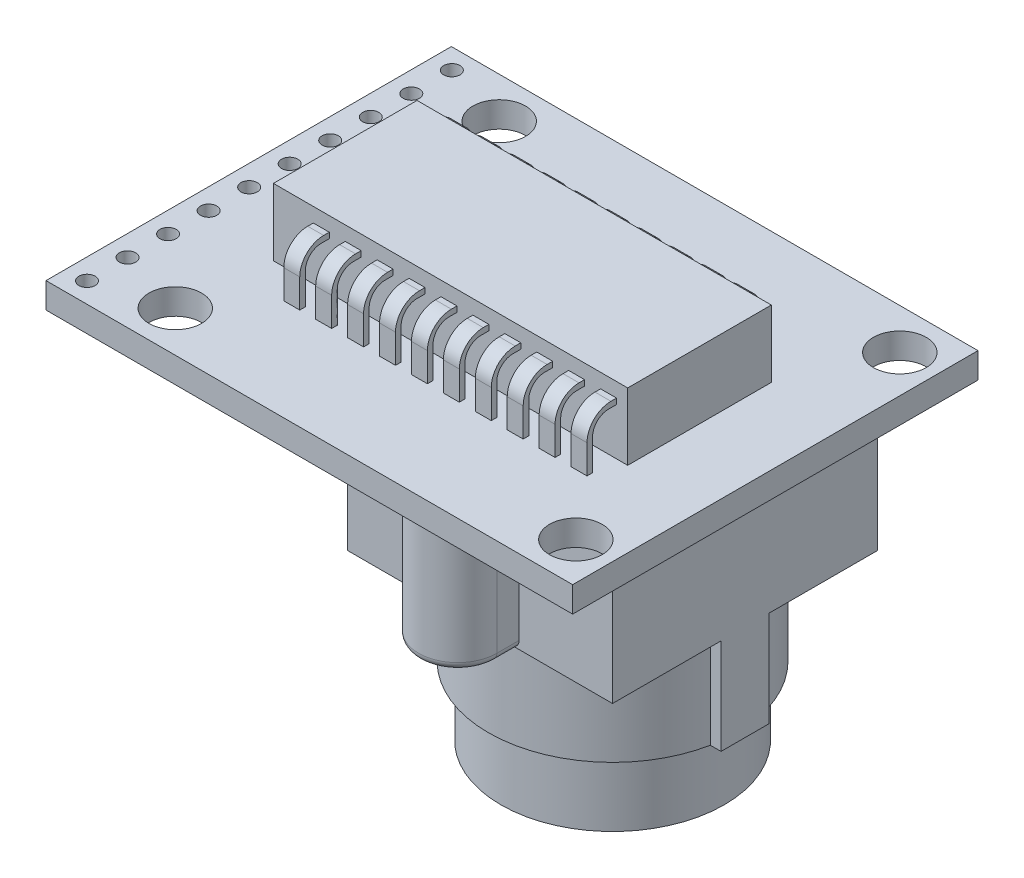
SolidWorks part; units mm, degrees
ref_plane "Alzado" through (0, 0, 0) normal (0, 0, 1) x (1, 0, 0)
ref_plane "Planta" through (0, 0, 0) normal (0, 1, 0) x (1, 0, 0)
ref_plane "Vista lateral" through (0, 0, 0) normal (1, 0, 0) x (0, 0, -1)
sketch "Croquis1" plane through (0, 0, 0) normal (0, 1, 0) x (1, 0, 0)
  line L0 (-6.0979, 0) -> (20.9271, 0) construction
  line L1 (-16.5, -12.7) -> (16.5, -12.7)
  line L2 (-16.5, -12.7) -> (-16.5, 12.7)
  line L3 (-16.5, 12.7) -> (16.5, 12.7)
  line L4 (16.5, -12.7) -> (16.5, 12.7)
  line L5 (-16.5, -12.7) -> (16.5, 12.7) construction
  line L6 (-16.5, 12.7) -> (16.5, -12.7) construction
  circle A0 centre (-15.2, 11.43) radius 0.51
  circle A1 centre (-15.2, 8.89) radius 0.51
  circle A2 centre (-15.2, 6.35) radius 0.51
  circle A3 centre (-15.2, 3.81) radius 0.51
  circle A4 centre (-15.2, 1.27) radius 0.51
  circle A5 centre (-15.2, -1.27) radius 0.51
  circle A6 centre (-15.2, -3.81) radius 0.51
  circle A7 centre (-15.2, -6.35) radius 0.51
  circle A8 centre (-15.2, -8.89) radius 0.51
  circle A9 centre (-15.2, -11.43) radius 0.51
  circle A10 centre (14.15, 10.15) radius 1.65
  circle A11 centre (14.15, -10.15) radius 1.65
  circle A12 centre (-10.95, 10.15) radius 1.65
  circle A13 centre (-10.95, -10.15) radius 1.65
  point P0 (0, 0)
  dimension "D3" = 1.02
  dimension "D4" = 1.3
  dimension "D5" = 1.27
  dimension "D7" = 3.3
  dimension "D8" = 2.35
  dimension "D9" = 2.55
  dimension "D10" = 3.3
  dimension "D11" = 5.55
  dimension "D12" = 2.55
  dimension "D1" = 25.4
  dimension "D2" = 33
  dimension "D6" = 10
extrude "Saliente-Extruir1" add sketch "Croquis1" along normal blind 1.6
sketch "Croquis2" plane through (0, 1.6, 0) normal (0, 1, 0) x (1, 0, 0)
  line L0 (-19.1826, 0) -> (21.3671, 0) construction
  line L1 (16.5, -12.7) -> (16.5, 12.7) construction
  line L2 (-10.45, -4.5) -> (11.75, -4.5)
  line L3 (-10.45, -4.5) -> (-10.45, 4.5)
  line L4 (-10.45, 4.5) -> (11.75, 4.5)
  line L5 (11.75, -4.5) -> (11.75, 4.5)
  line L6 (-10.45, -4.5) -> (11.75, 4.5) construction
  line L7 (-10.45, 4.5) -> (11.75, -4.5) construction
  point P3 (0.65, 0)
  dimension "D1" = 22.2
  dimension "D2" = 9
  dimension "D3" = 4.75
extrude "Saliente-Extruir2" add sketch "Croquis2" along normal blind 4.2
sketch "Croquis3" plane through (0, 1.6, 0) normal (0, 1, 0) x (1, 0, 0)
  line L0 (-10.45, -4.5) -> (11.75, -4.5) construction
  line L1 (10.05, -6) -> (11.05, -6)
  line L2 (10.05, -6) -> (10.05, -6.35)
  line L3 (10.05, -6.35) -> (11.05, -6.35)
  line L4 (11.05, -6) -> (11.05, -6.35)
  line L5 (11.75, -4.5) -> (11.75, 4.5) construction
  line L6 (8.05, -6) -> (8.05, -6.35)
  line L7 (8.05, -6) -> (9.05, -6)
  line L8 (9.05, -6) -> (9.05, -6.35)
  line L9 (8.05, -6.35) -> (9.05, -6.35)
  line L10 (6.05, -6) -> (6.05, -6.35)
  line L11 (6.05, -6) -> (7.05, -6)
  line L12 (7.05, -6) -> (7.05, -6.35)
  line L13 (6.05, -6.35) -> (7.05, -6.35)
  line L14 (4.05, -6) -> (4.05, -6.35)
  line L15 (4.05, -6) -> (5.05, -6)
  line L16 (5.05, -6) -> (5.05, -6.35)
  line L17 (4.05, -6.35) -> (5.05, -6.35)
  line L18 (2.05, -6) -> (2.05, -6.35)
  line L19 (2.05, -6) -> (3.05, -6)
  line L20 (3.05, -6) -> (3.05, -6.35)
  line L21 (2.05, -6.35) -> (3.05, -6.35)
  line L22 (0.05, -6) -> (0.05, -6.35)
  line L23 (0.05, -6) -> (1.05, -6)
  line L24 (1.05, -6) -> (1.05, -6.35)
  line L25 (0.05, -6.35) -> (1.05, -6.35)
  line L26 (-1.95, -6) -> (-1.95, -6.35)
  line L27 (-1.95, -6) -> (-0.95, -6)
  line L28 (-0.95, -6) -> (-0.95, -6.35)
  line L29 (-1.95, -6.35) -> (-0.95, -6.35)
  line L30 (-3.95, -6) -> (-3.95, -6.35)
  line L31 (-3.95, -6) -> (-2.95, -6)
  line L32 (-2.95, -6) -> (-2.95, -6.35)
  line L33 (-3.95, -6.35) -> (-2.95, -6.35)
  line L34 (-5.95, -6) -> (-5.95, -6.35)
  line L35 (-5.95, -6) -> (-4.95, -6)
  line L36 (-4.95, -6) -> (-4.95, -6.35)
  line L37 (-5.95, -6.35) -> (-4.95, -6.35)
  line L38 (-7.95, -6) -> (-7.95, -6.35)
  line L39 (-7.95, -6) -> (-6.95, -6)
  line L40 (-6.95, -6) -> (-6.95, -6.35)
  line L41 (-7.95, -6.35) -> (-6.95, -6.35)
  line L43 (-10.45, 4.5) -> (-10.45, -4.5) construction
  line L44 (-9.75, 6.35) -> (-8.75, 6.35)
  line L45 (-9.75, 6.35) -> (-9.75, 6)
  line L46 (-9.75, 6) -> (-8.75, 6)
  line L47 (-8.75, 6.35) -> (-8.75, 6)
  line L48 (11.75, 4.5) -> (-10.45, 4.5) construction
  line L49 (-7.75, 6.35) -> (-7.75, 6)
  line L50 (-7.75, 6.35) -> (-6.75, 6.35)
  line L51 (-6.75, 6.35) -> (-6.75, 6)
  line L52 (-7.75, 6) -> (-6.75, 6)
  line L53 (-5.75, 6.35) -> (-5.75, 6)
  line L54 (-5.75, 6.35) -> (-4.75, 6.35)
  line L55 (-4.75, 6.35) -> (-4.75, 6)
  line L56 (-5.75, 6) -> (-4.75, 6)
  line L57 (-3.75, 6.35) -> (-3.75, 6)
  line L58 (-3.75, 6.35) -> (-2.75, 6.35)
  line L59 (-2.75, 6.35) -> (-2.75, 6)
  line L60 (-3.75, 6) -> (-2.75, 6)
  line L61 (-1.75, 6.35) -> (-1.75, 6)
  line L62 (-1.75, 6.35) -> (-0.75, 6.35)
  line L63 (-0.75, 6.35) -> (-0.75, 6)
  line L64 (-1.75, 6) -> (-0.75, 6)
  line L65 (0.25, 6.35) -> (0.25, 6)
  line L66 (0.25, 6.35) -> (1.25, 6.35)
  line L67 (1.25, 6.35) -> (1.25, 6)
  line L68 (0.25, 6) -> (1.25, 6)
  line L69 (2.25, 6.35) -> (2.25, 6)
  line L70 (2.25, 6.35) -> (3.25, 6.35)
  line L71 (3.25, 6.35) -> (3.25, 6)
  line L72 (2.25, 6) -> (3.25, 6)
  line L73 (4.25, 6.35) -> (4.25, 6)
  line L74 (4.25, 6.35) -> (5.25, 6.35)
  line L75 (5.25, 6.35) -> (5.25, 6)
  line L76 (4.25, 6) -> (5.25, 6)
  line L77 (6.25, 6.35) -> (6.25, 6)
  line L78 (6.25, 6.35) -> (7.25, 6.35)
  line L79 (7.25, 6.35) -> (7.25, 6)
  line L80 (6.25, 6) -> (7.25, 6)
  line L81 (8.25, 6.35) -> (8.25, 6)
  line L82 (8.25, 6.35) -> (9.25, 6.35)
  line L83 (9.25, 6.35) -> (9.25, 6)
  line L84 (8.25, 6) -> (9.25, 6)
  dimension "D1" = 0.35
  dimension "D2" = 1
  dimension "D3" = 1.5
  dimension "D4" = 0.7
  dimension "D6" = 0.35
  dimension "D7" = 1
  dimension "D8" = 0.7
  dimension "D9" = 1.5
  dimension "D5" = 10
  dimension "D10" = 10
extrude "Saliente-Extruir3" add sketch "Croquis3" along normal blind 3.3
sketch "Croquis4" plane through (0, 0, 6) normal (0, 0, -1) x (-1, 0, 0)
  line L0 (-10.05, 4.9) -> (-10.05, 1.6) construction
  line L1 (-11.05, 4.9) -> (-10.05, 4.9)
  line L2 (-11.05, 4.9) -> (-11.05, 4.55)
  line L3 (-11.05, 4.55) -> (-10.05, 4.55)
  line L4 (-10.05, 4.9) -> (-10.05, 4.55)
  line L5 (-9.05, 4.9) -> (-9.05, 4.55)
  line L6 (-9.05, 4.9) -> (-8.05, 4.9)
  line L7 (-8.05, 4.9) -> (-8.05, 4.55)
  line L8 (-9.05, 4.55) -> (-8.05, 4.55)
  line L9 (-7.05, 4.9) -> (-7.05, 4.55)
  line L10 (-7.05, 4.9) -> (-6.05, 4.9)
  line L11 (-6.05, 4.9) -> (-6.05, 4.55)
  line L12 (-7.05, 4.55) -> (-6.05, 4.55)
  line L13 (-5.05, 4.9) -> (-5.05, 4.55)
  line L14 (-5.05, 4.9) -> (-4.05, 4.9)
  line L15 (-4.05, 4.9) -> (-4.05, 4.55)
  line L16 (-5.05, 4.55) -> (-4.05, 4.55)
  line L17 (-3.05, 4.9) -> (-3.05, 4.55)
  line L18 (-3.05, 4.9) -> (-2.05, 4.9)
  line L19 (-2.05, 4.9) -> (-2.05, 4.55)
  line L20 (-3.05, 4.55) -> (-2.05, 4.55)
  line L21 (-1.05, 4.9) -> (-1.05, 4.55)
  line L22 (-1.05, 4.9) -> (-0.05, 4.9)
  line L23 (-0.05, 4.9) -> (-0.05, 4.55)
  line L24 (-1.05, 4.55) -> (-0.05, 4.55)
  line L25 (0.95, 4.9) -> (0.95, 4.55)
  line L26 (0.95, 4.9) -> (1.95, 4.9)
  line L27 (1.95, 4.9) -> (1.95, 4.55)
  line L28 (0.95, 4.55) -> (1.95, 4.55)
  line L29 (2.95, 4.9) -> (2.95, 4.55)
  line L30 (2.95, 4.9) -> (3.95, 4.9)
  line L31 (3.95, 4.9) -> (3.95, 4.55)
  line L32 (2.95, 4.55) -> (3.95, 4.55)
  line L33 (4.95, 4.9) -> (4.95, 4.55)
  line L34 (4.95, 4.9) -> (5.95, 4.9)
  line L35 (5.95, 4.9) -> (5.95, 4.55)
  line L36 (4.95, 4.55) -> (5.95, 4.55)
  line L37 (6.95, 4.9) -> (6.95, 4.55)
  line L38 (6.95, 4.9) -> (7.95, 4.9)
  line L39 (7.95, 4.9) -> (7.95, 4.55)
  line L40 (6.95, 4.55) -> (7.95, 4.55)
  dimension "D1" = 0.35
  dimension "D2" = 10
extrude "Saliente-Extruir4" add sketch "Croquis4" along normal up to next
sketch "Croquis5" plane through (0, 0, -6) normal (0, 0, 1) x (1, 0, 0)
  line L0 (-8.75, 4.9) -> (-8.75, 1.6) construction
  line L1 (-9.75, 4.9) -> (-8.75, 4.9)
  line L2 (-9.75, 4.9) -> (-9.75, 4.55)
  line L3 (-9.75, 4.55) -> (-8.75, 4.55)
  line L4 (-8.75, 4.9) -> (-8.75, 4.55)
  line L5 (-7.75, 4.9) -> (-7.75, 4.55)
  line L6 (-7.75, 4.9) -> (-6.75, 4.9)
  line L7 (-6.75, 4.9) -> (-6.75, 4.55)
  line L8 (-7.75, 4.55) -> (-6.75, 4.55)
  line L9 (-5.75, 4.9) -> (-5.75, 4.55)
  line L10 (-5.75, 4.9) -> (-4.75, 4.9)
  line L11 (-4.75, 4.9) -> (-4.75, 4.55)
  line L12 (-5.75, 4.55) -> (-4.75, 4.55)
  line L13 (-3.75, 4.9) -> (-3.75, 4.55)
  line L14 (-3.75, 4.9) -> (-2.75, 4.9)
  line L15 (-2.75, 4.9) -> (-2.75, 4.55)
  line L16 (-3.75, 4.55) -> (-2.75, 4.55)
  line L17 (-1.75, 4.9) -> (-1.75, 4.55)
  line L18 (-1.75, 4.9) -> (-0.75, 4.9)
  line L19 (-0.75, 4.9) -> (-0.75, 4.55)
  line L20 (-1.75, 4.55) -> (-0.75, 4.55)
  line L21 (0.25, 4.9) -> (0.25, 4.55)
  line L22 (0.25, 4.9) -> (1.25, 4.9)
  line L23 (1.25, 4.9) -> (1.25, 4.55)
  line L24 (0.25, 4.55) -> (1.25, 4.55)
  line L25 (2.25, 4.9) -> (2.25, 4.55)
  line L26 (2.25, 4.9) -> (3.25, 4.9)
  line L27 (3.25, 4.9) -> (3.25, 4.55)
  line L28 (2.25, 4.55) -> (3.25, 4.55)
  line L29 (4.25, 4.9) -> (4.25, 4.55)
  line L30 (4.25, 4.9) -> (5.25, 4.9)
  line L31 (5.25, 4.9) -> (5.25, 4.55)
  line L32 (4.25, 4.55) -> (5.25, 4.55)
  line L33 (6.25, 4.9) -> (6.25, 4.55)
  line L34 (6.25, 4.9) -> (7.25, 4.9)
  line L35 (7.25, 4.9) -> (7.25, 4.55)
  line L36 (6.25, 4.55) -> (7.25, 4.55)
  line L37 (8.25, 4.9) -> (8.25, 4.55)
  line L38 (8.25, 4.9) -> (9.25, 4.9)
  line L39 (9.25, 4.9) -> (9.25, 4.55)
  line L40 (8.25, 4.55) -> (9.25, 4.55)
  dimension "D1" = 0.35
  dimension "D2" = 10
extrude "Saliente-Extruir5" add sketch "Croquis5" along normal up to next
fillet "Redondeo1" radius 1 20 edges at (-9.25, 4.55, -6) (-7.25, 4.55, -6) (-5.25, 4.55, -6) (-3.25, 4.55, -6) (-1.25, 4.55, -6) (0.75, 4.55, -6) (2.75, 4.55, -6) (4.75, 4.55, -6) (6.75, 4.55, -6) (8.75, 4.55, -6) (-5.45, 4.55, 6) (-7.45, 4.55, 6) (-1.45, 4.55, 6) (-3.45, 4.55, 6) (0.55, 4.55, 6) (4.55, 4.55, 6) (2.55, 4.55, 6) (8.55, 4.55, 6) (6.55, 4.55, 6) (10.55, 4.55, 6)
fillet "Redondeo2" radius 1.5 20 edges at (-7.45, 4.9, 6.35) (-5.45, 4.9, 6.35) (-3.45, 4.9, 6.35) (-1.45, 4.9, 6.35) (0.55, 4.9, 6.35) (2.55, 4.9, 6.35) (4.55, 4.9, 6.35) (6.55, 4.9, 6.35) (8.55, 4.9, 6.35) (10.55, 4.9, 6.35) (-9.25, 4.9, -6.35) (-7.25, 4.9, -6.35) (-5.25, 4.9, -6.35) (-3.25, 4.9, -6.35) (-1.25, 4.9, -6.35) (0.75, 4.9, -6.35) (2.75, 4.9, -6.35) (4.75, 4.9, -6.35) (6.75, 4.9, -6.35) (8.75, 4.9, -6.35)
sketch "Croquis6" plane through (0, 0, 0) normal (0, -1, 0) x (1, 0, 0)
  line L0 (-18.6365, 0) -> (22.3911, 0) construction
  line L1 (16.5, 12.7) -> (16.5, -12.7) construction
  line L2 (-2, -8.3) -> (3.85, -8.3)
  line L3 (-2, -8.3) -> (-2, 8.3)
  line L4 (-2, 8.3) -> (3.85, 8.3)
  line L5 (14.6, -8.3) -> (14.6, 8.3)
  line L6 (-2, -8.3) -> (14.6, 8.3) construction
  line L7 (-2, 8.3) -> (14.6, -8.3) construction
  line L8 (3.85, 9.7) -> (3.85, 8.3)
  line L9 (8.75, 9.7) -> (8.75, 8.3)
  line L10 (3.85, -9.7) -> (3.85, -8.3)
  line L11 (8.75, -9.7) -> (8.75, -8.3)
  line L12 (8.75, -8.3) -> (14.6, -8.3)
  line L13 (8.75, 8.3) -> (14.6, 8.3)
  arc A0 (8.75, 9.7) -> (3.85, 9.7) centre (6.3, 9.7) ccw
  arc A1 (8.75, -9.7) -> (3.85, -9.7) centre (6.3, -9.7) cw
  point P3 (6.3, 0)
  dimension "D4" = 4.9
  dimension "D5" = 9.7
  dimension "D1" = 16.6
  dimension "D2" = 16.6
  dimension "D3" = 18.5
extrude "Saliente-Extruir6" add sketch "Croquis6" along normal blind 8
fillet "Redondeo3" radius 0.5 6 edges at (3.85, -8, -9) (8.75, -8, -9) (6.3, -8, -12.15) (8.75, -8, 9) (3.85, -8, 9) (6.3, -8, 12.15)
sketch "Croquis7" plane through (0, -8, 0) normal (0, -1, 0) x (1, 0, 0)
  line L0 (-2, 0) -> (14.6, 0) construction
  line L1 (-2, 8.3) -> (-2, -8.3) construction
  line L2 (14.6, -8.3) -> (14.6, 8.3) construction
  line L3 (6.3, 12.15) -> (6.3, -12.15) construction
  line L4 (14.6, -8.3) -> (14.6, 8.3) construction
  line L8 (14.6, -1.5) -> (14.6, 1.5)
  line L12 (14.6, 1.5) -> (13.9289, 1.5)
  line L13 (14.6, -1.5) -> (13.9289, -1.5)
  arc A0 (8.75, 9.7) -> (3.85, 9.7) centre (6.3, 9.7) ccw construction
  arc A1 (3.85, -9.7) -> (8.75, -9.7) centre (6.3, -9.7) ccw construction
  arc A2 (13.9289, 1.5) -> (13.9289, -1.5) centre (6.3, 0) ccw
  point P16 (14.299, 0)
  dimension "D1" = 3
  dimension "15.45" = 15.55
extrude "Saliente-Extruir7" add sketch "Croquis7" along normal blind 6
sketch "Croquis8" plane through (0, -14, 0) normal (0, -1, 0) x (1, 0, 0)
  circle A0 centre (6.3, 0) radius 7
  dimension "D1" = 14
extrude "Saliente-Extruir8" add sketch "Croquis8" along normal blind 4.3
